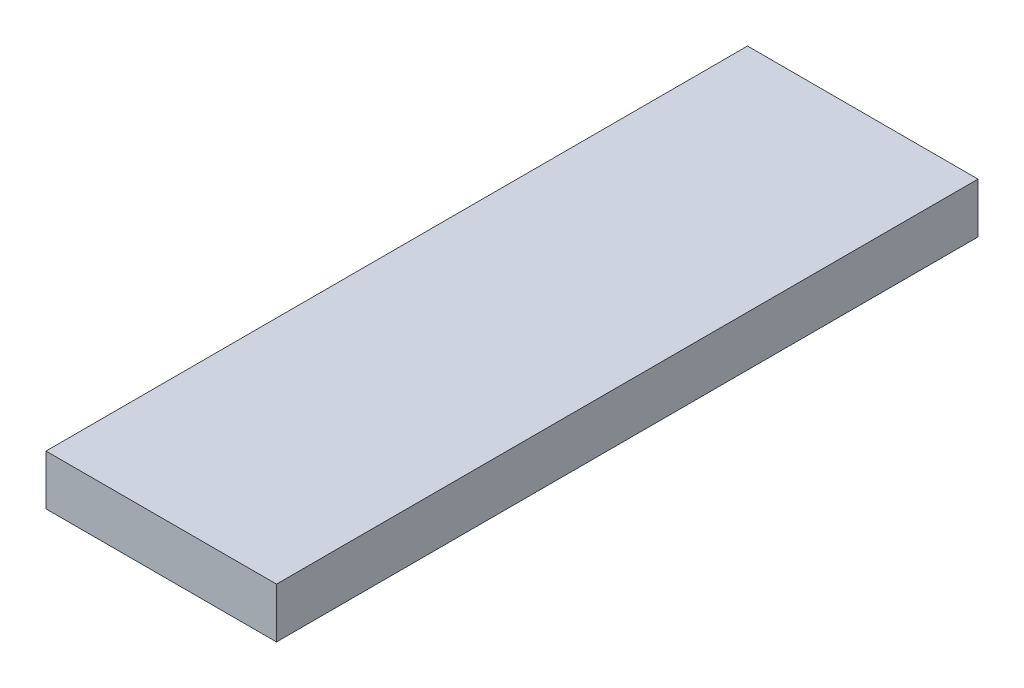
SolidWorks part; units mm, degrees
ref_plane "前视基准面" through (0, 0, 0) normal (0, 0, 1) x (1, 0, 0)
ref_plane "上视基准面" through (0, 0, 0) normal (0, 1, 0) x (1, 0, 0)
ref_plane "右视基准面" through (0, 0, 0) normal (1, 0, 0) x (0, 0, -1)
other "Configuration Table"
sketch "草图1" plane through (0, 0, 0) normal (0, 1, 0) x (1, 0, 0)
  line L1 (-11.5, 35) -> (11.5, 35)
  line L2 (-11.5, 35) -> (-11.5, -35)
  line L3 (-11.5, -35) -> (11.5, -35)
  line L4 (11.5, 35) -> (11.5, -35)
  line L5 (-11.5, 35) -> (11.5, -35) construction
  line L6 (-11.5, -35) -> (11.5, 35) construction
  point P0 (0, 0)
  dimension "D1" = 70
  dimension "D2" = 23
extrude "凸台-拉伸1" add sketch "草图1" along normal blind 5
